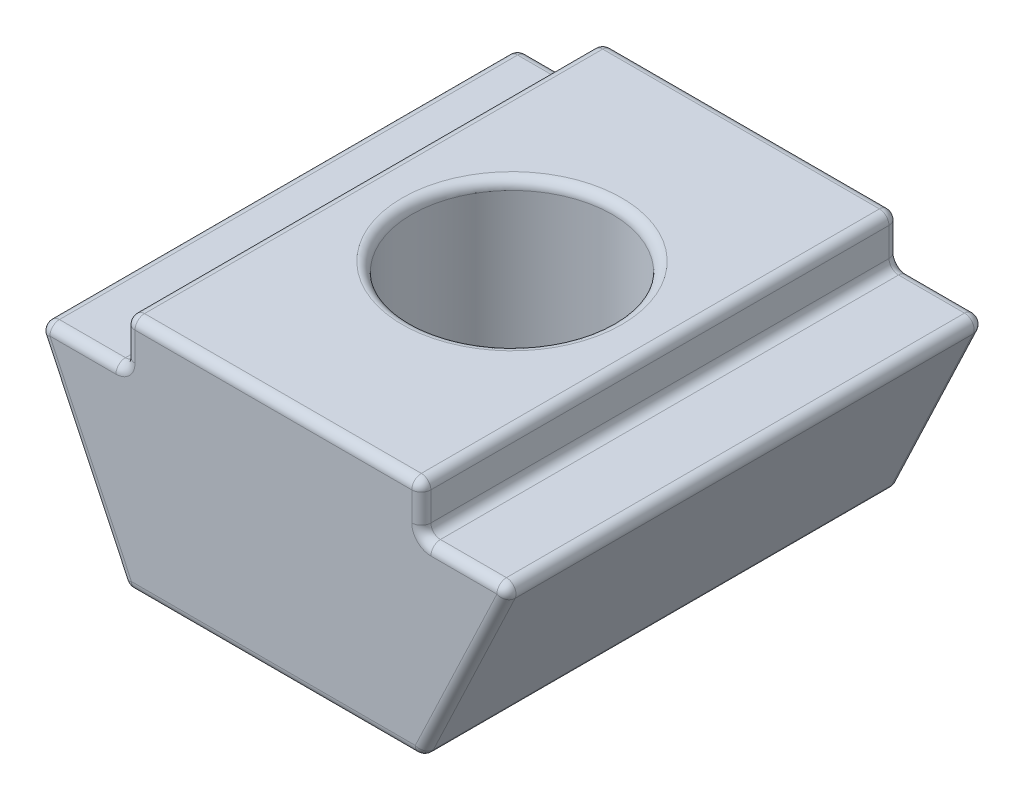
SolidWorks part; units mm, degrees
ref_plane "Front Plane" through (0, 0, 0) normal (0, 0, 1) x (1, 0, 0)
ref_plane "Top Plane" through (0, 0, 0) normal (0, 1, 0) x (1, 0, 0)
ref_plane "Right Plane" through (0, 0, 0) normal (1, 0, 0) x (0, 0, -1)
ref_plane "Rear Plane" through (0, 0, 10) normal (0, 0, 1) x (1, 0, 0)
sketch "MainSketch" plane through (0, 0, 0) normal (0, 0, 1) x (1, 0, 0)
  line L0 (-3.1, 0) -> (3.1, 0)
  line L1 (3.1, 0) -> (5, 4)
  line L2 (5, 4) -> (3.1, 4)
  line L3 (3.1, 4) -> (3.1, 5)
  line L4 (3.1, 5) -> (-3.1, 5)
  line L5 (-3.1, 5) -> (-3.1, 4)
  line L6 (-3.1, 4) -> (-5, 4)
  line L7 (-5, 4) -> (-3.1, 0)
  point P4 (0, 0)
  dimension "D1" = 4
  dimension "D2" = 5
  dimension "D3" = 6.2
  dimension "D4" = 10
extrude "NutExtrusion" add sketch "MainSketch" along normal up to surface (10 mm away) up to plane "Rear Plane"
sketch "HoleLocationSketch" plane through (0, 5, 0) normal (0, 1, 0) x (1, 0, 0)
  line L0 (-3.1, -10) -> (3.1, 0) construction
  line L1 (3.1, 0) -> (-3.1, 0) construction
  line L2 (3.1, -10) -> (3.1, 0) construction
  point P5 (0, -5)
hole_wizard "M5x0.8 Tapped Hole1" positions "Sketch3" profile "Sketch4" tap size "M5x0.8" standard "ANSI Metric" end condition through all
sketch "Sketch3" plane through (0, 5, 0) normal (0, 1, 0) x (1, 0, 0)
  point P0 (0, -5)
sketch "Sketch4" plane through (0, 5, 5) normal (1, 0, 0) x (0, 0, 1)
  line L0 (0, 0) -> (0, 5)
  line L1 (0, 5) -> (2.1, 5)
  line L2 (2.1, 5) -> (2.1, 0)
  line L5 (2.1, 0) -> (0, 0)
  line L11 (0, -6.35) -> (0, 107.95) construction
  dimension "Thru Tap Drill Dia." = 4.2
  dimension "Thru Tap Drill Depth" = 5
cosmetic thread "Hole Thread1" parameters "D2"=5
fillet "Fillet1" radius 0.2 26 edges at (4.05, 2, 10) (-3.1, 4.5, 10) (-3.1, 4, 5) (-4.05, 4, 10) (3.1, 0, 5) (0, 0, 10) (0, 0, 7.1) (-3.1, 0, 5) (-5, 4, 5) (-4.05, 2, 10) (-3.1, 4.5, 0) (-4.05, 4, 0) (-4.05, 2, 0) (0, 0, 0) (4.05, 2, 0) (3.1, 4.5, 0) (3.1, 4.5, 10) (-3.1, 5, 5) (0, 5, 0) (3.1, 5, 5) (0, 5, 10) (0, 5, 7.1) (3.1, 4, 5) (4.05, 4, 0) (5, 4, 5) (4.05, 4, 10)
